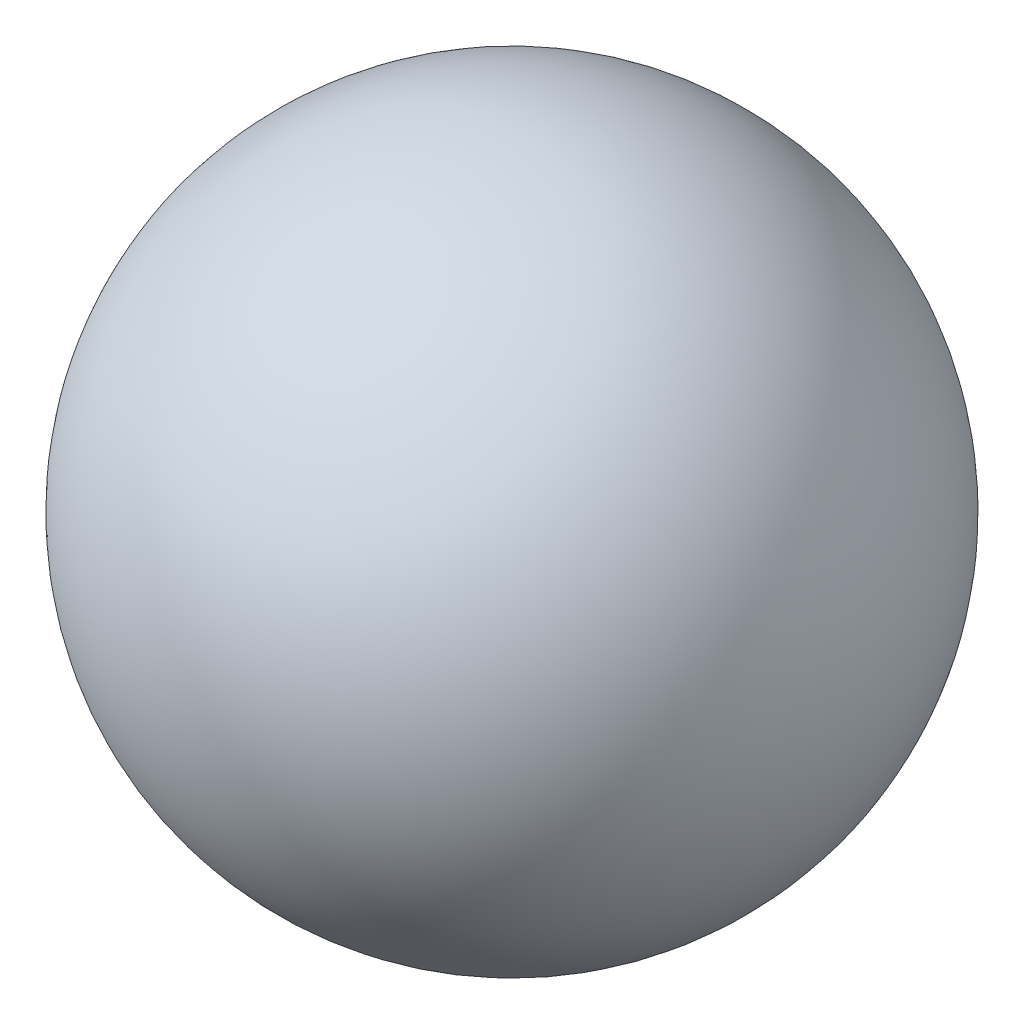
SolidWorks part; units mm, degrees
ref_plane "Plan de face" through (0, 0, 0) normal (0, 0, 1) x (1, 0, 0)
ref_plane "Plan de dessus" through (0, 0, 0) normal (0, 1, 0) x (1, 0, 0)
ref_plane "Plan de droite" through (0, 0, 0) normal (1, 0, 0) x (0, 0, -1)
sketch "Esquisse1" plane through (0, 0, 0) normal (0, 0, 1) x (1, 0, 0)
  line L0 (-12, 0) -> (12, 0)
  arc A0 (-12, 0) -> (12, 0) centre (0, 0) ccw
  dimension "D1" = 24
  dimension "D2" = 12
revolve "Révolution1" add sketch "Esquisse1" angle 360 about L0
